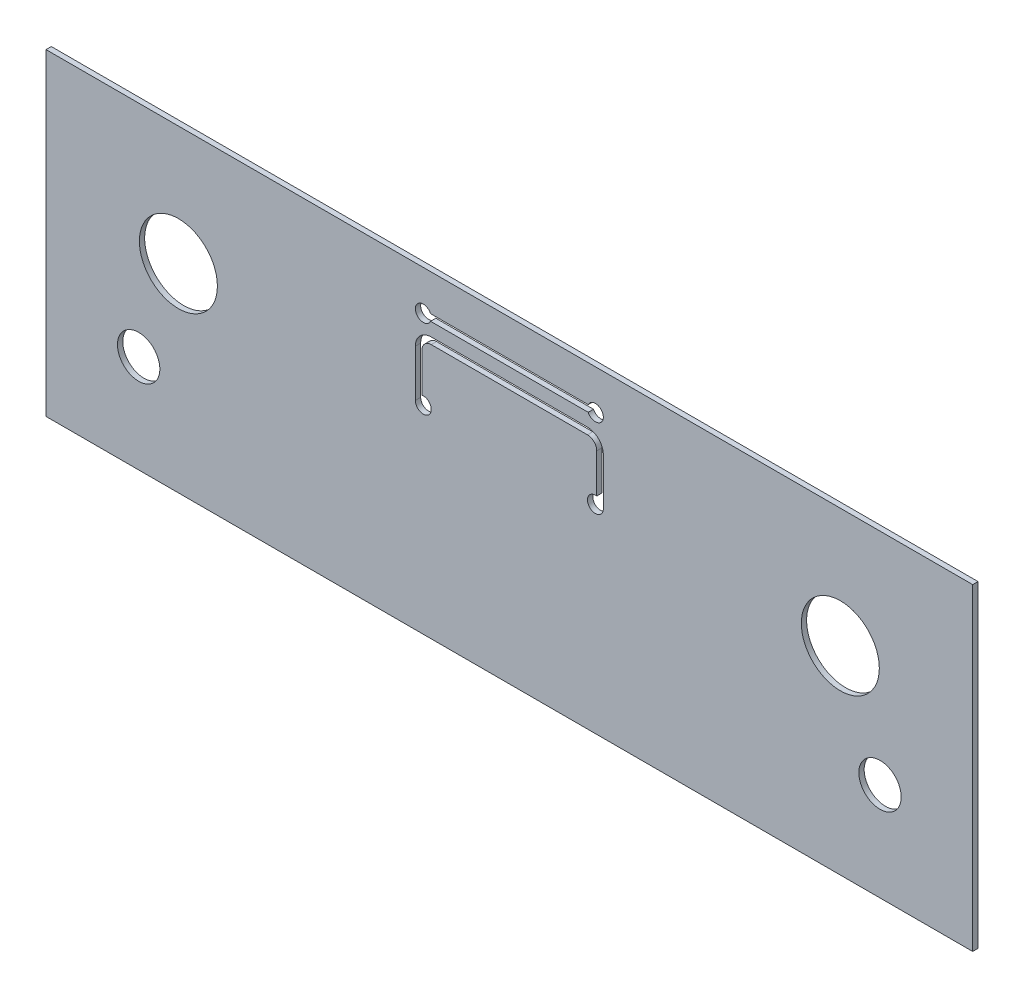
SolidWorks part; units mm, degrees
ref_plane "Front Plane" through (0, 0, 0) normal (0, 0, 1) x (1, 0, 0)
ref_plane "Top Plane" through (0, 0, 0) normal (0, 1, 0) x (1, 0, 0)
ref_plane "Right Plane" through (0, 0, 0) normal (1, 0, 0) x (0, 0, -1)
sketch "Sketch1" plane through (0, 0, 0) normal (0, 0, 1) x (1, 0, 0)
  line L0 (0, 0) -> (35, 0)
  line L1 (35, 0) -> (35, -12)
  line L2 (35, -12) -> (0, -12)
  line L3 (0, -12) -> (0, 0)
  line L4 (0, -6) -> (47.4455, -6) construction
  line L5 (17.5, 4.0959) -> (17.5, -15.1104) construction
  line L6 (14.5227, -1.375) -> (20.4773, -1.375)
  line L7 (14.5227, -1.625) -> (20.4773, -1.625)
  line L8 (13.95, -4.5) -> (13.95, -2.725)
  line L9 (14.55, -2.125) -> (20.45, -2.125)
  line L10 (21.05, -2.725) -> (21.05, -4.5)
  line L11 (14.2, -4.2042) -> (14.2, -2.725)
  line L12 (14.55, -2.375) -> (20.45, -2.375)
  line L13 (20.8, -2.725) -> (20.8, -4.2042)
  line L14 (14.55, -2.125) -> (14.55, -2.375) construction
  circle A0 centre (3.5, -8.3) radius 0.8001
  circle A1 centre (5, -4.5) radius 1.4732
  arc A2 (14.5227, -1.375) -> (14.5227, -1.625) centre (14.25, -1.5) ccw
  arc A3 (20.4773, -1.625) -> (20.4773, -1.375) centre (20.75, -1.5) ccw
  arc A4 (20.8, -4.2042) -> (21.05, -4.5) centre (20.75, -4.5) ccw
  arc A5 (13.95, -4.5) -> (14.2, -4.2042) centre (14.25, -4.5) ccw
  circle A6 centre (30, -4.5) radius 1.4732
  circle A7 centre (31.5, -8.3) radius 0.8001
  arc A8 (13.95, -2.725) -> (14.55, -2.125) centre (14.55, -2.725) cw
  arc A9 (20.45, -2.125) -> (21.05, -2.725) centre (20.45, -2.725) cw
  arc A10 (14.2, -2.725) -> (14.55, -2.375) centre (14.55, -2.725) cw
  arc A11 (20.45, -2.375) -> (20.8, -2.725) centre (20.45, -2.725) cw
  point P14 (17.5, 0)
  point P46 (14.55, -2.25)
  dimension "D3" = 1.6002
  dimension "D5" = 6.5
  dimension "D13" = 3
  dimension "D18" = 3.5
  dimension "D34" = 2.9464
  dimension "D10" = 0.25
  dimension "D14" = 1.5
  dimension "D20" = 3.5
  dimension "D12" = 0.6
  dimension "D15" = 0.3
  dimension "D1" = 35
  dimension "D2" = 12
  dimension "D4" = 8.3
  dimension "D6" = 14.25
  dimension "D7" = 0.25
  dimension "D8" = 0.75
  dimension "D9" = 0.25
  dimension "D11" = 0.25
  dimension "D16" = 4.5
  dimension "D17" = 5
  dimension "D19" = 5
extrude "Boss-Extrude1" add sketch "Sketch1" along normal blind 0.2
